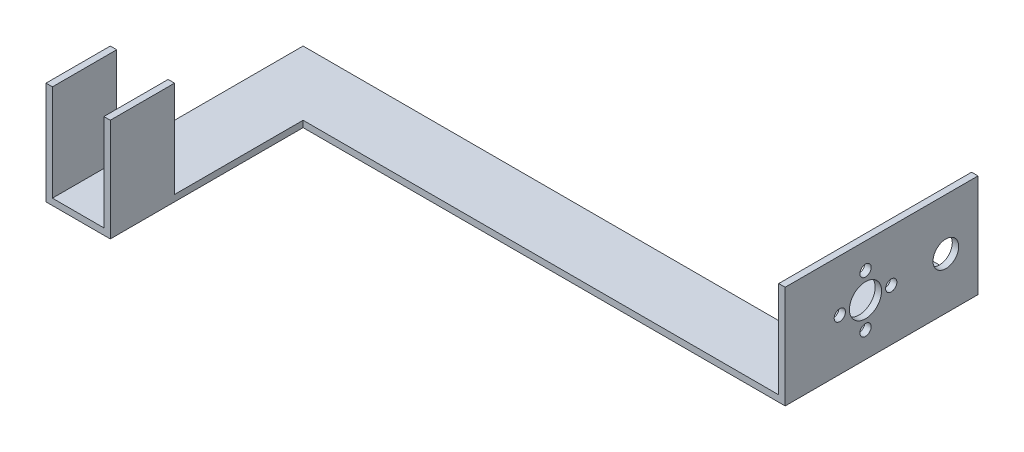
SolidWorks part; units mm, degrees
ref_plane "Front Plane" through (0, 0, 0) normal (0, 0, 1) x (1, 0, 0)
ref_plane "Top Plane" through (0, 0, 0) normal (0, 1, 0) x (1, 0, 0)
ref_plane "Right Plane" through (0, 0, 0) normal (1, 0, 0) x (0, 0, -1)
sketch "Sketch1" plane through (0, 0, 0) normal (0, 1, 0) x (1, 0, 0)
  line L0 (150, 120) -> (150, 60)
  line L1 (150, 60) -> (0, 60)
  line L2 (0, 60) -> (0, 0)
  line L3 (0, 0) -> (-20, 0)
  line L4 (-20, 0) -> (-20, 80)
  line L5 (-20, 80) -> (130, 80)
  line L6 (130, 80) -> (130, 120)
  line L7 (130, 120) -> (150, 120)
  dimension "D1" = 80
  dimension "D2" = 170
  dimension "D3" = 150
  dimension "D4" = 20
  dimension "D5" = 60
  dimension "D6" = 20
extrude "Boss-Extrude1" add sketch "Sketch1" along normal blind 2
sketch "Sketch2" plane through (0, 2, 0) normal (0, 1, 0) x (1, 0, 0)
  line L0 (-20, 0) -> (-20, 20)
  line L1 (-20, 80) -> (-20, 0) construction
  line L2 (-20, 20) -> (-18, 20)
  line L3 (-18, 20) -> (-18, 0)
  line L4 (-20, 0) -> (0, 0) construction
  line L5 (-18, 0) -> (-20, 0)
  line L6 (-10, 0) -> (-10, 47.1363) construction
  line L7 (-2, 0) -> (0, 0)
  line L8 (-2, 20) -> (-2, 0)
  line L9 (0, 20) -> (-2, 20)
  line L10 (0, 0) -> (0, 20)
  line L17 (150, 60) -> (150, 120)
  line L18 (150, 120) -> (148, 120)
  line L19 (150, 120) -> (130, 120) construction
  line L20 (148, 120) -> (148, 60)
  line L21 (0, 60) -> (150, 60) construction
  line L22 (148, 60) -> (150, 60)
  dimension "D1" = 2
  dimension "D2" = 20
  dimension "D3" = 2
extrude "Boss-Extrude2" add sketch "Sketch2" along normal blind 30
sketch "Sketch3" plane through (150, 0, 0) normal (1, 0, 0) x (0, 0, -1)
  line L0 (60, 32) -> (60, 0) construction
  line L1 (60, 32) -> (120, 32) construction
  circle A0 centre (85, 16) radius 8 construction
  circle A1 centre (85, 16) radius 5
  circle A2 centre (85, 24) radius 1.75
  circle A3 centre (93, 16) radius 1.75
  circle A4 centre (85, 8) radius 1.75
  circle A5 centre (77, 16) radius 1.75
  circle A6 centre (110, 16) radius 4
  dimension "D1" = 16
  dimension "D2" = 10
  dimension "D4" = 3.5
  dimension "D7" = 8
  dimension "D8" = 25
  dimension "D3" = 25
  dimension "D6" = 16
  dimension "D5" = 4
extrude "Cut-Extrude1" cut sketch "Sketch3" against normal up to next
